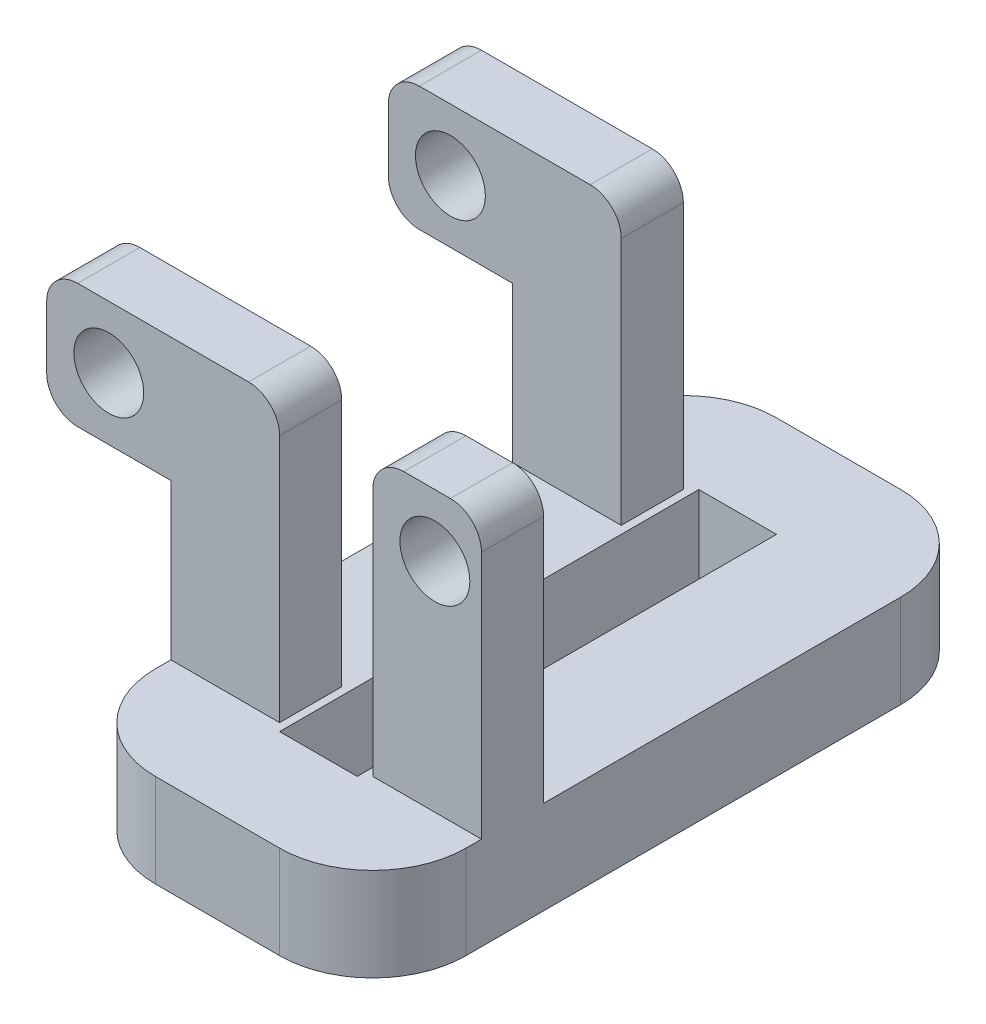
SolidWorks part; units mm, degrees
ref_plane "Front" through (0, 0, 0) normal (0, 0, 1) x (1, 0, 0)
ref_plane "Top" through (0, 0, 0) normal (0, 1, 0) x (1, 0, 0)
ref_plane "Right" through (0, 0, 0) normal (1, 0, 0) x (0, 0, -1)
sketch "Croquis1" plane through (0, 0, 0) normal (0, 1, 0) x (1, 0, 0)
  line L0 (-223.043, 0) -> (10929.1056, 0) construction
  line L1 (0, -223.043) -> (0, 10929.1056) construction
  line L2 (-223.043, -2.5) -> (10929.1056, -2.5) construction
  line L3 (-2, -10) -> (2, -10)
  line L4 (-5, -7) -> (-5, 7)
  line L5 (-2, 10) -> (2, 10)
  line L6 (5, -7) -> (5, 7)
  line L7 (-5, -10) -> (5, 10) construction
  line L8 (-5, 10) -> (5, -10) construction
  line L9 (-223.043, 2.5) -> (10929.1056, 2.5) construction
  line L11 (-1.25, -6.75) -> (1.25, -6.75)
  line L12 (-1.25, -6.75) -> (-1.25, 6.75)
  line L13 (-1.25, 6.75) -> (1.25, 6.75)
  line L14 (1.25, -6.75) -> (1.25, 6.75)
  line L15 (-1.25, -6.75) -> (1.25, 6.75) construction
  line L16 (-1.25, 6.75) -> (1.25, -6.75) construction
  arc A0 (-5, 7) -> (-2, 10) centre (-2, 7) cw
  arc A1 (-2, -10) -> (-5, -7) centre (-2, -7) cw
  arc A2 (5, 7) -> (2, 10) centre (2, 7) ccw
  arc A3 (5, -7) -> (2, -10) centre (2, -7) cw
  point P4 (0, 0)
  point P22 (0, 0)
  point P32 (0.6, 0)
  dimension "D3" = 3
  dimension "D4" = 3
  dimension "D5" = 3
  dimension "D6" = 3
  dimension "D7" = 13.5
  dimension "D8" = 2.5
  dimension "D1" = 20
  dimension "D2" = 10
  dimension "D9" = 2.5
  dimension "D10" = 2.5
extrude "Saliente-Extruir1" add sketch "Croquis1" along normal blind 3
sketch "Croquis2" plane through (0, 3, 0) normal (0, 1, 0) x (1, 0, 0)
  line L0 (0, -1000) -> (0, 49000) construction
  line L1 (-1000, 0) -> (49000, 0) construction
  line L2 (-1000, -6.5) -> (49000, -6.5) construction
  line L3 (-1000, 6.5) -> (49000, 6.5) construction
  line L4 (5, -1000) -> (5, 49000) construction
  line L5 (-7, -1000) -> (-7, 49000) construction
  line L6 (-5, 6.5) -> (-1.5, 6.5)
  line L7 (-1.5, 6.5) -> (-1.5, 4.5)
  line L8 (-1.5, 4.5) -> (-5, 4.5)
  line L9 (-5, 4.5) -> (-5, 6.5)
  line L10 (-5, -4.5) -> (-5, -6.5)
  line L11 (-1.5, -4.5) -> (-5, -4.5)
  line L12 (-1.5, -6.5) -> (-1.5, -4.5)
  line L13 (-5, -6.5) -> (-1.5, -6.5)
  line L14 (5, -4.5) -> (5, -6.5)
  line L15 (5, -6.5) -> (1.5, -6.5)
  line L16 (1.5, -6.5) -> (1.5, -4.5)
  line L17 (1.5, -4.5) -> (5, -4.5)
  point P16 (-3.25, 6.5)
  dimension "D5" = 3.5
  dimension "D6" = 2
  dimension "D7" = 1.5
  dimension "D1" = 6.5
  dimension "D2" = 6.5
  dimension "D3" = 5
extrude "Saliente-Extruir2" add sketch "Croquis2" along normal blind 9
sketch "Croquis3" plane through (0, 0, 6.5) normal (0, 0, 1) x (1, 0, 0)
  line L2 (0, -1000) -> (0, 49000) construction
  line L3 (1.5, 12) -> (5, 12) construction
  line L5 (1.5, 12) -> (1.5, 3) construction
  circle A1 centre (3.5, 10) radius 1.125
  dimension "D1" = 2
  dimension "D2" = 2
extrude "Cortar-Extruir1" cut sketch "Croquis3" against normal up to surface (13 mm away) up to face at (-3.25, 7.5, -6.5)
sketch "Croquis4" plane through (0, 0, 6.5) normal (0, 0, 1) x (1, 0, 0)
  line L0 (-3.25, -993) -> (-3.25, 49007) construction
  line L1 (-5, 12) -> (-1.5, 12) construction
  line L2 (-1007.7153, 10.45) -> (48992.2847, 10.45) construction
  line L4 (-1.5, 12) -> (-1.5, 3) construction
  line L5 (-5, 12) -> (-1.5, 12)
  line L6 (-5, 12) -> (-5, 10.45)
  line L7 (-5, 10.45) -> (-1.5, 10.45)
  line L8 (-1.5, 12) -> (-1.5, 10.45)
  point P5 (-3.25, 12)
  dimension "D1" = 1.55
extrude "Cortar-Extruir2" [suppressed] cut sketch "Croquis4" against normal up to surface (13 mm away)
fillet "Redondeo1" [suppressed] radius 2
sketch "Croquis5" plane through (-5, 0, 0) normal (-1, 0, 0) x (0, 0, 1)
  line L0 (6.5, 12) -> (6.5, 3) construction
  line L1 (4.5, 12) -> (6.5, 12)
  line L2 (4.5, 12) -> (4.5, 8)
  line L3 (4.5, 8) -> (6.5, 8)
  line L4 (6.5, 12) -> (6.5, 8)
  line L5 (0, -1000) -> (0, 49000) construction
  line L6 (-7, 0) -> (7, 0) construction
  line L7 (-4.5, 12) -> (-4.5, 8)
  line L8 (-4.5, 8) -> (-6.5, 8)
  line L9 (-6.5, 12) -> (-6.5, 8)
  line L10 (-4.5, 12) -> (-6.5, 12)
  point P12 (0, 0)
  dimension "D1" = 4
extrude "Saliente-Extruir3" add sketch "Croquis5" along normal blind 4
sketch "Croquis6" plane through (0, 0, 6.5) normal (0, 0, 1) x (1, 0, 0)
  line L0 (-5, 8) -> (-9, 12) construction
  line L1 (-9, 8) -> (-5.25, 12) construction
  line L2 (-9, 12) -> (-1.5, 12) construction
  circle A0 centre (-7, 10) radius 1.125
  dimension "D1" = 2.25
extrude "Cortar-Extruir3" cut sketch "Croquis6" against normal through all
fillet "Redondeo2" radius 1 8 edges at (5, 12, 5.5) (-9, 8, 5.5) (-1.5, 12, 5.5) (-9, 12, 5.5) (-1.5, 12, -5.5) (-9, 8, -5.5) (-9, 12, -5.5) (1.5, 12, 5.5)
